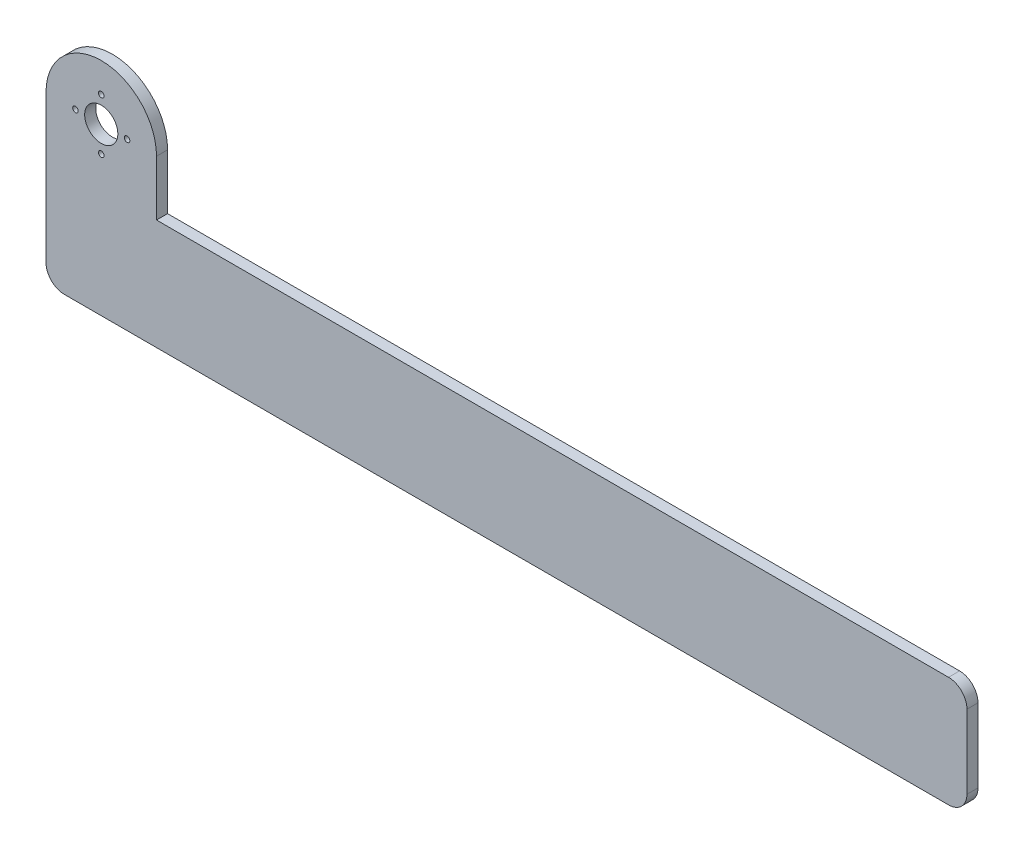
SolidWorks part; units mm, degrees
material "Aleación 1060"
ref_plane "Alzado" through (0, 0, 0) normal (0, 0, 1) x (1, 0, 0)
ref_plane "Planta" through (0, 0, 0) normal (0, 1, 0) x (1, 0, 0)
ref_plane "Vista lateral" through (0, 0, 0) normal (1, 0, 0) x (0, 0, -1)
sketch "Croquis1" plane through (0, 0, 0) normal (0, 0, 1) x (1, 0, 0)
  line L0 (30, -45) -> (470, -45)
  line L2 (-30, 45) -> (-30, -45)
  line L3 (-30, -45) -> (30, -45)
  line L4 (30, 45) -> (30, 15)
  line L5 (-30, 45) -> (30, -45) construction
  line L6 (-30, -45) -> (30, 45) construction
  line L7 (470, -45) -> (470, 15)
  line L8 (470, 15) -> (30, 15)
  arc A0 (-30, 45) -> (30, 45) centre (0, 45) cw
  point P0 (0, 0)
  dimension "D1" = 90
  dimension "6" = 30
  dimension "D2" = 60
  dimension "D3" = 500
  dimension "D4" = 30
extrude "Saliente-Extruir1" add sketch "Croquis1" along normal blind 6
fillet "Redondeo1" radius 10 1 edges at (-30, -45, 3)
fillet "Redondeo2" radius 10 2 edges at (470, -45, 3) (470, 15, 3)
sketch "Croquis2" plane through (0, 0, 6) normal (0, 0, 1) x (1, 0, 0)
  circle A0 centre (0, 45) radius 9
  dimension "D1" = 18
extrude "Cortar-Extruir1" cut sketch "Croquis2" against normal through all
sketch "Croquis3" plane through (0, 0, 6) normal (0, 0, 1) x (1, 0, 0)
  line L0 (30, 15) -> (30, 45) construction
  line L1 (-30, 45) -> (-30, -35) construction
  circle A0 centre (0, 31) radius 1.5
  circle A1 centre (14, 45) radius 1.5
  circle A2 centre (0, 59) radius 1.5
  circle A3 centre (-14, 45) radius 1.5
  arc A4 (30, 45) -> (-30, 45) centre (0, 45) ccw construction
  dimension "D2" = 3
  dimension "D4" = 3
  dimension "D5" = 3
  dimension "D8" = 3
  dimension "D1" = 14
  dimension "D3" = 14
  dimension "D6" = 14
  dimension "D7" = 14
  dimension "D9" = 16
  dimension "D10" = 30
extrude "Cortar-Extruir2" cut sketch "Croquis3" against normal through all
